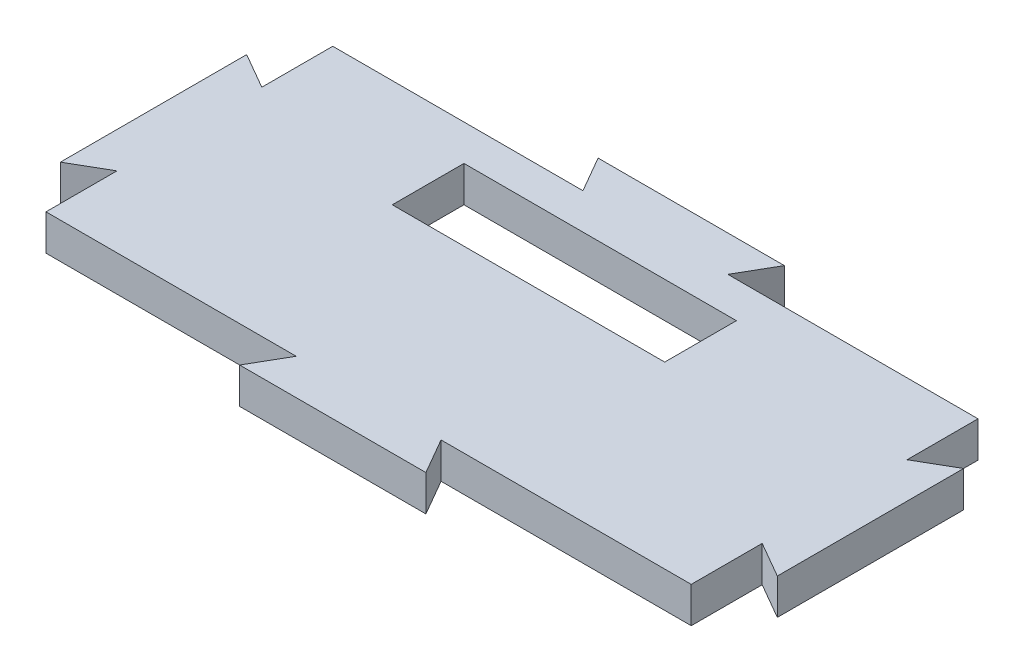
SolidWorks part; units mm, degrees
ref_plane "Front Plane" through (0, 0, 0) normal (1, 0, 0) x (0, 1, 0)
ref_plane "Top Plane" through (0, 0, 0) normal (0, 0, 1) x (0, 1, 0)
ref_plane "Right Plane" through (0, 0, 0) normal (0, 1, 0) x (-1, 0, 0)
sketch "Sketch2" plane through (0, 0, 0) normal (0, 1, 0) x (-1, 0, 0)
  line L0 (-50, -12.9904) -> (-50, 12.9904)
  line L1 (-45, -20) -> (45, -20)
  line L2 (-45, -20) -> (-45, 20)
  line L3 (-45, 20) -> (45, 20)
  line L4 (45, -20) -> (45, 20)
  line L5 (-45, -20) -> (45, 20) construction
  line L6 (-45, 20) -> (45, -20) construction
  line L7 (-50, 12.9904) -> (-27.5, 0)
  line L8 (-27.5, 0) -> (-50, -12.9904)
  line L9 (0, 55) -> (0, -55) construction
  line L10 (50, 12.9904) -> (27.5, 0)
  line L11 (27.5, 0) -> (50, -12.9904)
  line L12 (50, -12.9904) -> (50, 12.9904)
  line L13 (12.9904, 25) -> (-12.9904, 25)
  line L14 (-12.9904, 25) -> (0, 2.5)
  line L15 (0, 2.5) -> (12.9904, 25)
  line L16 (55, 0) -> (-55, 0) construction
  line L17 (0, -2.5) -> (12.9904, -25)
  line L18 (-12.9904, -25) -> (0, -2.5)
  line L19 (12.9904, -25) -> (-12.9904, -25)
  circle A0 centre (-42.5, 0) radius 7.5
  circle A1 centre (42.5, 0) radius 7.5
  circle A2 centre (0, 17.5) radius 7.5
  circle A3 centre (0, -17.5) radius 7.5
  point P0 (0, 0)
  dimension "D5" = 15
  dimension "D6" = 15
  dimension "D1" = 40
  dimension "D2" = 90
  dimension "D3" = 5
  dimension "D4" = 20
  dimension "D7" = 45
  dimension "D8" = 5
extrude "Boss-Extrude1" add sketch "Sketch2" along normal blind 5 contours L11 L10 L4 L3 L2 L7 L8 L1 | A1 L4 | L11 A1 L10 | L13 L14 L15 | L17 L19 L18
sketch "Sketch3" plane through (0, 5, 0) normal (0, 1, 0) x (-1, 0, 0)
  line L0 (-16.3, -7.5296) -> (-16.3, -15)
  line L1 (-16.3, -15) -> (21.7, -15)
  line L2 (21.7, -15) -> (21.7, -5)
  line L8 (-16.3, -5) -> (-16.3, -7.5296)
  line L9 (-45, 10.1036) -> (-45, 20) construction
  line L11 (45, -20) -> (45, -10.1036) construction
  line L12 (-45, -20) -> (-10.1036, -20) construction
  line L14 (-16.3, -5) -> (21.7, -5)
  dimension "D1" = 38
  dimension "D4" = 10
  dimension "D5" = 10
  dimension "D7" = 28.7
  dimension "D8" = 23.3
  dimension "D9" = 5
extrude "Cut-Extrude1" cut sketch "Sketch3" against normal blind 10
